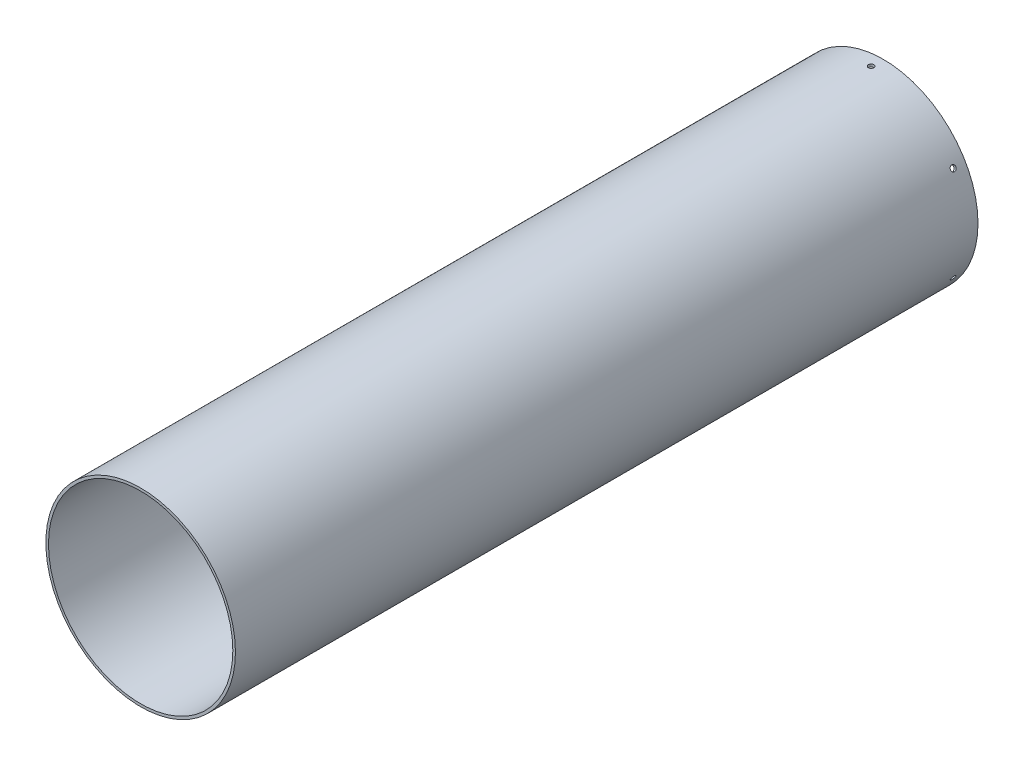
SolidWorks part; units mm, degrees
material "A-Glass Fiber"
ref_plane "Front Plane" through (0, 0, 0) normal (0, 0, 1) x (1, 0, 0)
ref_plane "Top Plane" through (0, 0, 0) normal (0, 1, 0) x (1, 0, 0)
ref_plane "Right Plane" through (0, 0, 0) normal (1, 0, 0) x (0, 0, -1)
sketch "Sketch1" plane through (0, 0, 0) normal (0, 0, 1) x (1, 0, 0)
  circle A0 centre (0, 0) radius 76.2
  circle A1 centre (0, 0) radius 78.359
  dimension "D1" = 156.718
  dimension "D2" = 152.4
extrude "Boss-Extrude1" add sketch "Sketch1" along normal blind 613.8
sketch "Sketch4" plane through (0, 0, 0) normal (0, 1, 0) x (1, 0, 0)
  line L0 (78.359, 0) -> (-78.359, 0) construction
  point P0 (0, -10)
  dimension "D1" = 10
hole_wizard "M4 Clearance Hole2" positions "Sketch4" profile "Sketch5" hole size "M4" standard "ANSI Metric"
sketch "Sketch5" plane through (0, 0, 10) normal (1, 0, 0) x (0, 0, -1)
  line L0 (0, 0) -> (0, 78.359)
  line L1 (0, 78.359) -> (2.25, 78.359)
  line L2 (2.25, 78.359) -> (2.25, 0)
  line L5 (2.25, 0) -> (0, 0)
  line L11 (0, -6.35) -> (0, 107.95) construction
  dimension "Thru Hole Dia." = 4.5
  dimension "Thru Hole Depth" = 78.359
pattern_circular "CirPattern2" count 6 over 360 about axis through (0, 0, 613.8) along (0, 0, -1) of "M4 Clearance Hole2"
